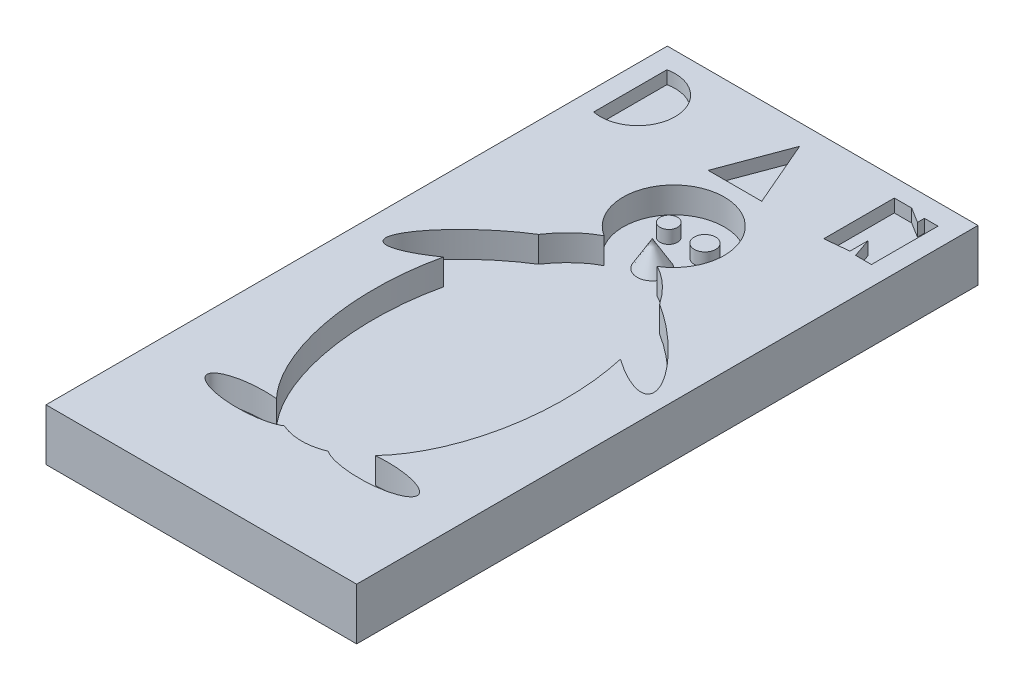
SolidWorks part; units mm, degrees
ref_plane "Front Plane" through (0, 0, 0) normal (0, 0, 1) x (1, 0, 0)
ref_plane "Top Plane" through (0, 0, 0) normal (0, 1, 0) x (1, 0, 0)
ref_plane "Right Plane" through (0, 0, 0) normal (1, 0, 0) x (0, 0, -1)
sketch "Sketch1" plane through (0, 0, 0) normal (0, 1, 0) x (1, 0, 0)
  line L1 (0, 0) -> (76.2, 0)
  line L2 (0, 0) -> (0, 152.4)
  line L3 (0, 152.4) -> (76.2, 152.4)
  line L4 (76.2, 0) -> (76.2, 152.4)
extrude "Boss-Extrude1" add sketch "Sketch1" along normal blind 12.7
sketch "Sketch2" plane through (0, 12.7, 0) normal (0, 1, 0) x (1, 0, 0)
  line L0 (39.0546, 105.9701) -> (39.0546, 82.4643) construction
  arc A0 (45.5543, 104.3483) -> (32.5548, 104.3483) centre (39.0546, 114.9191) ccw
  ellipse E0 centre (39.0546, 64.805) end of major axis (39.0546, 105.9701) minor radius 23.3866 (33.6693, 24.7461) -> (44.4398, 24.7461) ccw
  ellipse E1 centre (19.5674, 87.5644) end of major axis (6.5018, 76.1521) minor radius 4.4766 (24.1993, 96.5986) -> (17.3476, 80.1239) ccw
  ellipse E2 centre (58.5417, 87.5644) end of major axis (71.6073, 76.1521) minor radius 4.4766 (53.9098, 96.5986) -> (60.7615, 80.1239) cw
  ellipse E3 centre (24.0203, 26.2649) end of major axis (13.2816, 26.2649) minor radius 3.4603 (26.9386, 29.595) -> (33.6693, 24.7461) ccw
  ellipse E4 centre (54.0888, 26.2649) end of major axis (64.8275, 26.2649) minor radius 3.4603 (51.1705, 29.595) -> (44.4398, 24.7461) cw
  ellipse E5 centre (39.0546, 64.805) end of major axis (39.0546, 105.9701) minor radius 23.3866 (51.1705, 29.595) -> (60.7615, 80.1239) ccw
  ellipse E6 centre (39.0546, 64.805) end of major axis (39.0546, 105.9701) minor radius 23.3866 (53.9098, 96.5986) -> (45.5543, 104.3483) ccw
  ellipse E7 centre (39.0546, 64.805) end of major axis (39.0546, 105.9701) minor radius 23.3866 (17.3476, 80.1239) -> (26.9386, 29.595) ccw
  ellipse E8 centre (39.0546, 64.805) end of major axis (39.0546, 105.9701) minor radius 23.3866 (32.5548, 104.3483) -> (24.1993, 96.5986) ccw
extrude "Cut-Extrude1" cut sketch "Sketch2" against normal blind 6.35
sketch "Sketch4" plane through (0, 6.35, 0) normal (0, 1, 0) x (1, 0, 0)
  line L0 (32.5548, 104.3483) -> (45.5543, 104.3483) construction
  line L1 (45.5543, 104.3483) -> (39.0546, 104.3483) construction
  line L2 (39.0546, 104.3483) -> (39.0546, 127.3283) construction
  arc A0 (45.5543, 104.3483) -> (32.5548, 104.3483) centre (39.0546, 114.9191) ccw construction
  circle A1 centre (39.0546, 109.669) radius 3.7448
sketch "Sketch5" plane through (0, 12.7, 0) normal (0, 1, 0) x (1, 0, 0)
  point P0 (39.0546, 109.669)
loft "Loft1" add profiles "Sketch4", "Sketch5"
sketch "Sketch6" plane through (0, 6.35, 0) normal (0, 1, 0) x (1, 0, 0)
  circle A0 centre (34.4451, 118.3139) radius 2.1477
  circle A1 centre (43.3132, 118.3139) radius 2.625
extrude "Boss-Extrude2" add sketch "Sketch6" along normal blind 3.175
sketch "Sketch7" plane through (0, 12.7, 0) normal (0, 1, 0) x (1, 0, 0)
  line L0 (31.416, 131.0087) -> (37.5152, 147.3378)
  line L1 (4.9751, 147.3302) -> (4.9751, 129.3606)
  line L2 (65.9498, 131.2294) -> (65.9498, 135.7027)
  line L3 (37.5152, 147.3378) -> (44.5507, 131.0087)
  line L4 (65.9498, 135.7027) -> (67.5418, 131.0302)
  line L5 (44.5507, 131.0087) -> (41.033, 131.0087)
  line L9 (33.9022, 131.0087) -> (31.416, 131.0087)
  line L10 (71.4414, 131.0087) -> (71.4414, 147.3378)
  line L11 (71.4414, 147.3378) -> (68.1167, 147.3378)
  line L12 (68.1167, 147.3378) -> (68.1167, 145.6421)
  line L13 (68.1167, 145.6421) -> (66.9668, 146.3533)
  line L14 (66.9668, 146.3533) -> (64.3689, 147.9601)
  line L15 (64.3689, 147.9601) -> (60.1134, 147.9601)
  line L16 (60.1134, 147.9601) -> (60.1134, 130.6539)
  line L17 (60.1134, 130.6539) -> (65.9498, 131.2294)
  line L18 (67.5418, 131.0302) -> (71.4414, 131.0087)
  line L19 (33.9022, 131.0087) -> (41.033, 131.0087)
  arc A0 (4.9751, 129.3606) -> (4.9751, 147.3302) centre (6.7974, 138.3454) ccw
extrude "Cut-Extrude2" cut sketch "Sketch7" against normal blind 3.175
